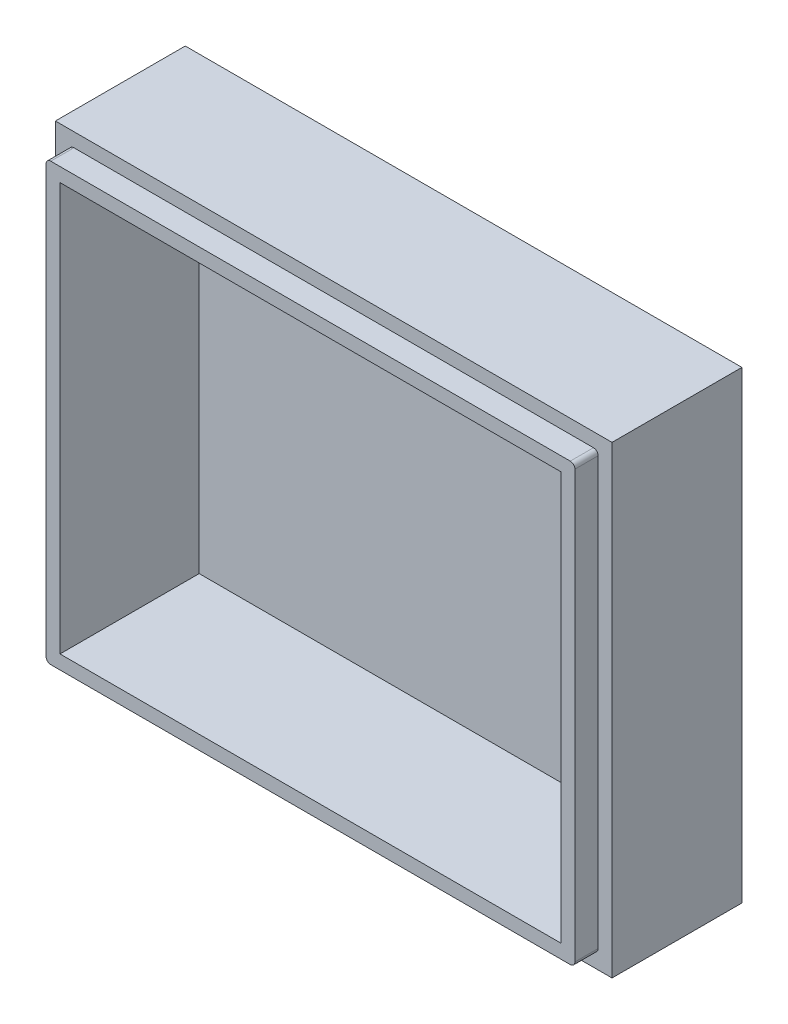
SolidWorks part; units mm, degrees
ref_plane "Alzado" through (0, 0, 0) normal (0, 0, 1) x (1, 0, 0)
ref_plane "Planta" through (0, 0, 0) normal (0, 1, 0) x (1, 0, 0)
ref_plane "Vista lateral" through (0, 0, 0) normal (1, 0, 0) x (0, 0, -1)
sketch "Croquis1" plane through (0, 0, 0) normal (0, 0, 1) x (1, 0, 0)
  line L0 (0, 0) -> (0, 100)
  line L1 (0, 100) -> (120, 100)
  line L2 (120, 100) -> (120, 0)
  line L3 (120, 0) -> (0, 0)
extrude "Saliente-Extruir1" add sketch "Croquis1" along normal blind 3
sketch "Croquis3" plane through (0, 0, 3) normal (0, 0, 1) x (1, 0, 0)
  line L1 (0, 100) -> (120, 100)
  line L2 (0, 100) -> (0, 0)
  line L3 (0, 0) -> (120, 0)
  line L4 (120, 100) -> (120, 0)
  line L6 (3, 97) -> (117, 97)
  line L7 (117, 97) -> (117, 3)
  line L8 (117, 3) -> (3, 3)
  line L9 (3, 3) -> (3, 97)
extrude "Saliente-Extruir2" add sketch "Croquis3" along normal blind 25
sketch "Croquis4" plane through (0, 0, 3) normal (0, 0, 1) x (1, 0, 0)
  line L1 (3, 97) -> (117, 97)
  line L2 (3, 97) -> (3, 3)
  line L3 (3, 3) -> (117, 3)
  line L4 (117, 97) -> (117, 3)
  line L6 (6, 94) -> (114, 94)
  line L7 (114, 94) -> (114, 6)
  line L8 (114, 6) -> (6, 6)
  line L9 (6, 6) -> (6, 94)
extrude "Saliente-Extruir3" add sketch "Croquis4" along normal blind 30
fillet "Redondeo1" radius 1 4 edges at (3, 3, 30.5) (117, 3, 30.5) (3, 97, 30.5) (117, 97, 30.5)
